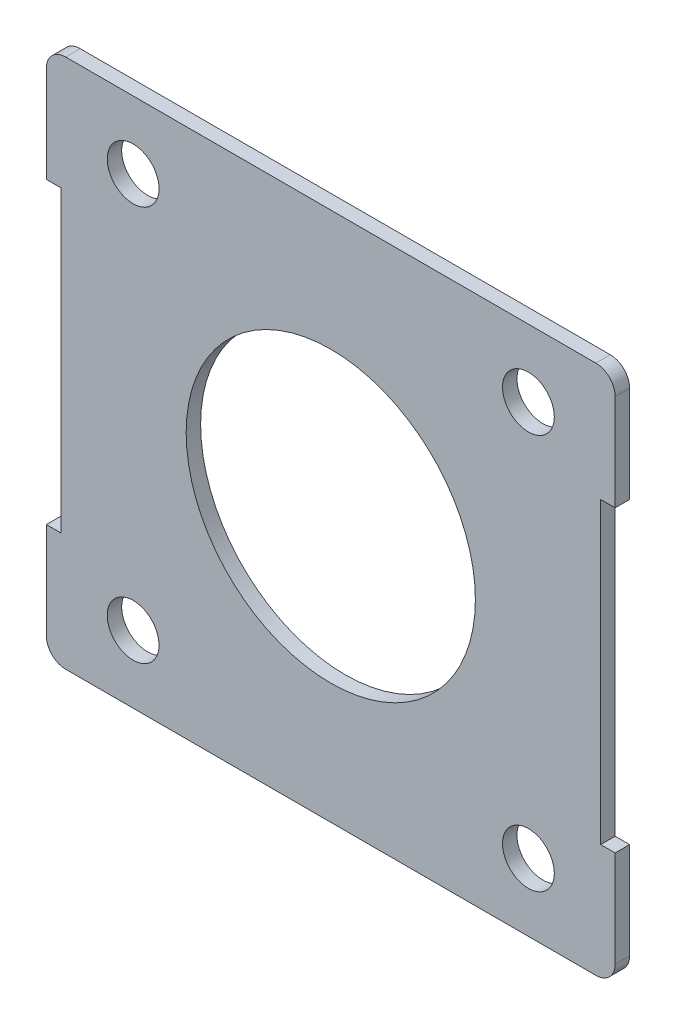
SolidWorks part; units mm, degrees
ref_plane "Front Plane" through (0, 0, 0) normal (0, 0, 1) x (1, 0, 0)
ref_plane "Top Plane" through (0, 0, 0) normal (0, 1, 0) x (1, 0, 0)
ref_plane "Right Plane" through (0, 0, 0) normal (1, 0, 0) x (0, 0, -1)
sketch "Sketch1" plane through (0, 0, 0) normal (0, 0, 1) x (1, 0, 0)
  line L0 (87.3125, 87.3125) -> (-87.3125, 87.3125) construction
  line L1 (-93.6625, 87.3125) -> (93.6625, 87.3125)
  line L2 (-93.6625, 87.3125) -> (-93.6625, -87.3125)
  line L3 (-93.6625, -87.3125) -> (93.6625, -87.3125)
  line L4 (93.6625, 87.3125) -> (93.6625, -87.3125)
  line L5 (93.6625, -108.2196) -> (93.6625, -49.2125) construction
  line L6 (-93.6625, -49.2125) -> (-93.6625, -108.2196) construction
  line L7 (0, 87.3125) -> (0, -87.3125) construction
extrude "Extrude1" add sketch "Sketch1" along normal blind 4.7625
sketch "Sketch2" plane through (0, 0, 4.7625) normal (0, 0, 1) x (1, 0, 0)
  line L0 (-93.6625, 87.3125) -> (-93.6625, -87.3125) construction
  line L1 (-93.6625, 49.2125) -> (-88.9, 49.2125)
  line L2 (-93.6625, 49.2125) -> (-93.6625, -49.2125)
  line L3 (-93.6625, -49.2125) -> (-88.9, -49.2125)
  line L4 (-88.9, 49.2125) -> (-88.9, -49.2125)
  line L5 (93.6625, -87.3125) -> (93.6625, 87.3125) construction
  line L6 (93.6625, 49.2125) -> (88.9, 49.2125)
  line L7 (93.6625, 49.2125) -> (93.6625, -49.2125)
  line L8 (93.6625, -49.2125) -> (88.9, -49.2125)
  line L9 (88.9, 49.2125) -> (88.9, -49.2125)
extrude "Cut-Extrude1" cut sketch "Sketch2" against normal up to next
fillet "Fillet1" radius 6.35 4 edges at (93.6625, -87.3125, 2.3813) (93.6625, 87.3125, 2.3813) (-93.6625, -87.3125, 2.3813) (-93.6625, 87.3125, 2.3813)
sketch "Sketch3" plane through (0, 0, 4.7625) normal (0, 0, 1) x (1, 0, 0)
  circle A0 centre (0, 0) radius 47.625
  circle A1 centre (-65.0875, 65.0875) radius 8.5328
  circle A2 centre (-65.0875, -65.0875) radius 8.5328
  circle A3 centre (65.0875, -65.0875) radius 8.5328
  circle A4 centre (65.0875, 65.0875) radius 8.5328
  circle A5 centre (65.0875, 65.0875) radius 8.5328 construction
  circle A6 centre (-65.0875, 65.0875) radius 8.5328 construction
  circle A7 centre (-65.0875, -65.0875) radius 8.5328 construction
  circle A8 centre (65.0875, -65.0875) radius 8.5328 construction
  circle A9 centre (0, 0) radius 47.625 construction
extrude "Cut-Extrude2" cut sketch "Sketch3" against normal up to next
